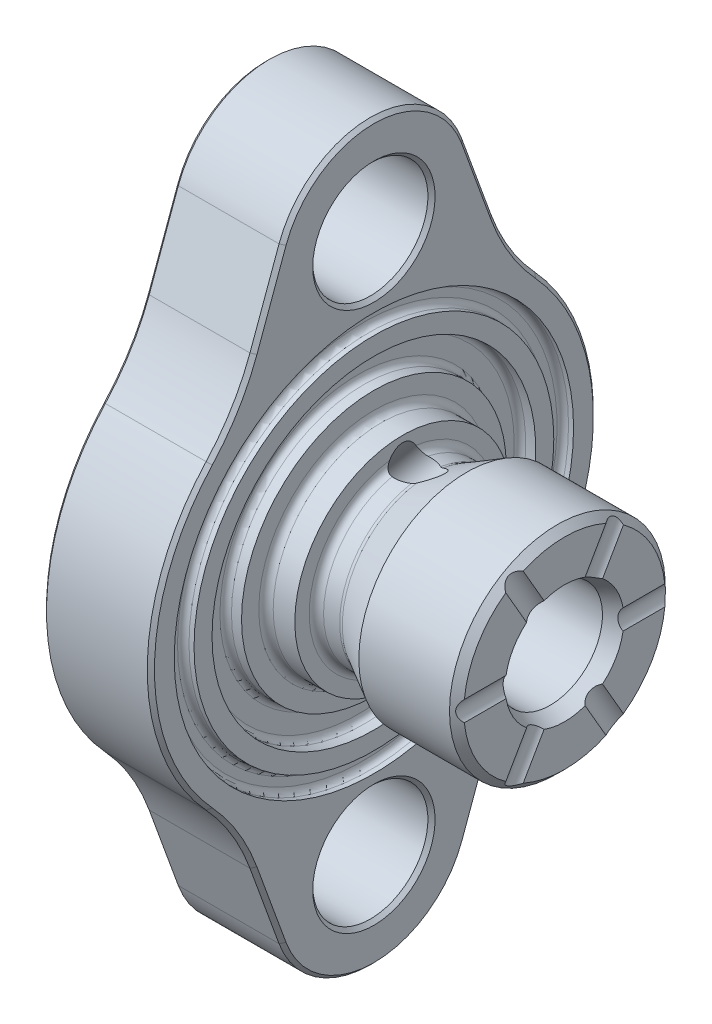
SolidWorks part; units mm, degrees
material "17CrNiMo6"
ref_plane "Front Plane" through (0, 0, 0) normal (0, 0, 1) x (1, 0, 0)
ref_plane "Top Plane" through (0, 0, 0) normal (0, 1, 0) x (1, 0, 0)
ref_plane "Right Plane" through (0, 0, 0) normal (1, 0, 0) x (0, 0, -1)
sketch "Sketch1" plane through (0, 0, 0) normal (0, 0, 1) x (1, 0, 0)
  line L0 (0, 0) -> (0, 52.5)
  line L1 (0, 52.5) -> (15, 52.5)
  line L2 (15, 52.5) -> (15, 27.75)
  line L3 (15, 27.75) -> (14.3, 27.75)
  line L4 (13.5, 26.95) -> (13.5, 25.8)
  line L5 (14.3, 25) -> (15, 25)
  line L6 (15, 25) -> (15, 22.5)
  line L7 (15, 22.5) -> (13.6, 22.5)
  line L8 (12.8, 21.7) -> (12.8, 19.2)
  line L9 (13.6, 18.4) -> (15, 18.4)
  line L10 (15, 18.4) -> (15, 15.9975)
  line L11 (16, 14.9975) -> (19, 14.9975)
  line L12 (19, 14.9975) -> (19, 13)
  line L13 (20, 12) -> (22.2411, 12)
  line L14 (22.7264, 12.1257) -> (27.9, 14.9975)
  line L15 (27.9, 14.9975) -> (41.5, 14.9975)
  line L16 (41.5, 14.9975) -> (41.5, 8.25)
  line L17 (41.5, 8.25) -> (39.5, 7.265)
  line L18 (39.5, 7.265) -> (30, 7.265)
  line L19 (30, 7.265) -> (30, 7.5)
  line L20 (30, 7.5) -> (28.5, 7.5)
  line L21 (28.5, 7.5) -> (27.9082, 6.515)
  line L22 (27.9082, 6.515) -> (19, 6.515)
  line L23 (19, 6.515) -> (19, 6.9)
  line L24 (12.5, 6.9) -> (8.5163, 0)
  line L25 (0, 0) -> (64.1591, 0) construction
  line L26 (19, 6.9) -> (12.5, 6.9)
  line L27 (0, 0) -> (8.5163, 0)
  arc A0 (14.3, 27.75) -> (13.5, 26.95) centre (14.3, 26.95) ccw
  arc A1 (14.3, 25) -> (13.5, 25.8) centre (14.3, 25.8) cw
  arc A2 (13.6, 22.5) -> (12.8, 21.7) centre (13.6, 21.7) ccw
  arc A3 (13.6, 18.4) -> (12.8, 19.2) centre (13.6, 19.2) cw
  arc A4 (20, 12) -> (19, 13) centre (20, 13) cw
  arc A5 (22.7264, 12.1257) -> (22.2411, 12) centre (22.2411, 13) cw
  arc A6 (16, 14.9975) -> (15, 15.9975) centre (16, 15.9975) cw
  point P25 (21, 12)
  point P42 (22.5, 12)
  dimension "D29" = 0.8
  dimension "D30" = 1
  dimension "D31" = 1
  dimension "D1" = 60
  dimension "D2" = 15
  dimension "D3" = 105
  dimension "D4" = 11.5
  dimension "D5" = 14.53
  dimension "D6" = 13.8
  dimension "D7" = 15
  dimension "D8" = 29.995
  dimension "D9" = 24
  dimension "D10" = 26.5
  dimension "D11" = 13
  dimension "D12" = 59
  dimension "D13" = 2
  dimension "D14" = 16.5
  dimension "D15" = 13.03
  dimension "D16" = 29
  dimension "D17" = 22.5
  dimension "D18" = 13.6
  dimension "D19" = 19
  dimension "D20" = 36.8
  dimension "D21" = 45
  dimension "D22" = 50
  dimension "D23" = 55.5
  dimension "D24" = 1.5
  dimension "D25" = 2.2
  dimension "D26" = 2
  dimension "D27" = 41.5
  dimension "D28" = 22.5
  dimension "D32" = 32.9837
revolve "Revolve1" add sketch "Sketch1" angle 360 about L25
sketch "Sketch2" plane through (0, 0, 0) normal (-1, 0, 0) x (0, 0, 1)
  line L0 (0, 0) -> (70.5057, 0) construction
  line L1 (0, 0) -> (0, 55.746) construction
  line L2 (12.6859, 42.1173) -> (16.7286, 31.0098)
  line L3 (-12.6859, 42.1173) -> (-16.7286, 31.0098)
  line L4 (12.6859, -42.1173) -> (16.7286, -31.0098)
  line L5 (-12.6859, -42.1173) -> (-16.7286, -31.0098)
  arc A0 (12.6859, 42.1173) -> (-12.6859, 42.1173) centre (0, 37.5) ccw
  arc A1 (22.8279, -20.9735) -> (22.8279, 20.9735) centre (0, 0) ccw
  arc A2 (22.8279, 20.9735) -> (16.7286, 31.0098) centre (44.9194, 41.2704) cw
  arc A3 (-22.8279, 20.9735) -> (-16.7286, 31.0098) centre (-44.9194, 41.2704) ccw
  arc A4 (-22.8279, -20.9735) -> (-22.8279, 20.9735) centre (0, 0) cw
  arc A5 (22.8279, -20.9735) -> (16.7286, -31.0098) centre (44.9194, -41.2704) ccw
  arc A6 (12.6859, -42.1173) -> (-12.6859, -42.1173) centre (0, -37.5) cw
  arc A7 (-22.8279, -20.9735) -> (-16.7286, -31.0098) centre (-44.9194, -41.2704) cw
  circle A8 centre (0, 37.5) radius 8 construction
  circle A9 centre (0, -37.5) radius 8 construction
  dimension "D1" = 27
  dimension "D2" = 62
  dimension "D3" = 75
  dimension "D5" = 30
  dimension "D6" = 102
  dimension "D7" = 16
  dimension "D4" = 20
extrude "Cut-Extrude1" cut sketch "Sketch2" against normal through all flip side to cut
sketch "Sketch3" plane through (0, 0, 0) normal (-1, 0, 0) x (0, 0, 1)
  circle A0 centre (0, 37.5) radius 8
  dimension "D1" = 16
extrude "Cut-Extrude2" cut sketch "Sketch3" against normal through all
mirror "Mirror1" about plane through (0, 0, 0) normal (0, 1, 0) of "Cut-Extrude2"
hole_wizard "CENTRE Hole1" positions "Sketch7" profile "Sketch6" legacy
sketch "Sketch7" plane through (0, 0, 0) normal (-1, 0, 0) x (0, 0, 1)
  point P0 (0, 0)
sketch "Sketch6" plane through (0, 0, 0) normal (0, 1, 0) x (0, 0, 1)
  line L0 (0, 0) -> (0, 6.2017)
  line L1 (0, 6.2017) -> (2, 5)
  line L2 (2, 5) -> (2, 1.7321)
  line L3 (2, 1.7321) -> (3, 0)
  line L4 (3, 0) -> (0, 0)
  line L5 (0, -14.3089) -> (0, 102.4216) construction
  line L6 (0, 6.2017) -> (-2, 5) construction
  line L7 (-2, 1.7321) -> (-3, 0) construction
  dimension "Diameter" = 4
  dimension "Depth" = 5
  dimension "C-Sink Diameter" = 6
  dimension "C-Sink Angle" = 60
  dimension "Drill Angle" = 118
chamfer "Chamfer2" distance 1 angle 45 1 edges at (41.5, 0, 14.9975)
sketch "Sketch8" plane through (0, 0, 0) normal (0, 0, 1) x (1, 0, 0)
  line L0 (0, 0) -> (52.9452, 0) construction
  line L2 (45.4183, -1.4) -> (41.5, -1.4)
  line L3 (45.4183, -1.4) -> (45.4183, 1.4)
  line L4 (45.4183, 1.4) -> (41.5, 1.4)
  line L5 (40.9283, -1.4) -> (40.9283, 1.4) construction
  line L6 (41.5, 1.4) -> (41.5, -1.4) construction
  line L7 (41.5, -13.9975) -> (41.5, 13.9975) construction
  arc A0 (41.5, 1.4) -> (41.5, -1.4) centre (42.9283, 0) ccw
  dimension "D2" = 2
  dimension "D1" = 2.8
extrude "Cut-Extrude4" cut sketch "Sketch8" against normal through all
ref_axis "Axis1" through (30, 0, 0) along (1, 0, 0)
pattern_circular "CirPattern1" count 6 over 360 about axis through (30, 0, 0) along (1, 0, 0) of "Cut-Extrude4"
ref_plane "Plane1" through (0, 0, 0) normal (0.6428, 0.766, 0) x (0, 0, -1)
ref_plane "Plane2" through (14.5855, 17.3824, 0) normal (0.6428, 0.766, 0) x (0, 0, -1)
sketch "Sketch14" plane through (0, 0, 0) normal (0, 0, 1) x (1, 0, 0)
  line L0 (20.5, 12) -> (10.4308, 0) construction
  line L1 (0, 0) -> (45.7767, 0) construction
  line L2 (41.5, 12.7614) -> (41.5, 7.7411) construction
  line L4 (0, 0) -> (64.1591, 0) construction
  line L5 (20, 12) -> (22.2411, 12) construction
  line L6 (25.8044, 14.4322) -> (15.5826, 2.2504)
  line L7 (25.8044, 14.4322) -> (23.8893, 16.0392)
  line L8 (15.5826, 2.2504) -> (12.3191, 2.2504)
  line L9 (23.8893, 16.0392) -> (12.3191, 2.2504)
  dimension "D1" = 50
  dimension "D2" = 21
  dimension "D3" = 5
  dimension "D4" = 5.2728
  dimension "D5" = 18
revolve "Cut-Revolve1" cut sketch "Sketch14" angle 360 about L9
pattern_circular "CirPattern2" count 2 over 360 about axis through (30, 0, 0) along (1, 0, 0) of "Cut-Revolve1"
sketch "Sketch13" plane through (0, 0, 0) normal (-1, 0, 0) x (0, 0, 1)
  line L0 (8, 16.3705) -> (8, -17.6011) construction
  line L1 (12.8425, 6.2687) -> (12.8425, -4.52) construction
  text T0 "3115 2076 03 - A\r\n11111 - XX" font "Century Gothic" height 3
  line B0 (12.8425, -2.4498) -> (12.8425, 1.4724)
  line B1 (13.642, -1.8688) -> (13.642, 1.0177)
  line B2 (12.9625, 1.4041) -> (13.522, 1.086)
  line B3 (16.9756, -0.0372) -> (16.9756, 0.6468)
  line B4 (19.6923, 1.4724) -> (16.9756, -0.0372)
  line B5 (13.642, -1.8688) -> (16.2187, -0.4475)
  line B6 (16.2187, -3.6028) -> (15.5991, -3.9613)
  line B7 (19.6923, -0.4525) -> (19.6923, 1.4724)
  line B8 (16.9756, -3.19) -> (16.2187, -3.6028)
  line B9 (16.9756, -3.19) -> (18.7235, -2.1534)
  line B10 (12.8425, 1.4724) -> (12.8425, 4.4693)
  line B11 (15.8055, 2.7844) -> (12.8425, 4.4693)
  line B12 (16.3391, -3.4279) -> (16.8556, -3.1217)
  line B13 (19.5723, -0.4525) -> (19.5723, 1.2684)
  line B14 (19.5723, 1.2684) -> (16.9756, -0.1745)
  line B15 (16.8556, 0.6468) -> (16.8556, -3.1217)
  line B16 (15.7434, 2.6817) -> (12.9625, 4.263)
  line B17 (12.9625, 1.5422) -> (12.9625, 4.263)
  line B18 (16.3391, -0.3779) -> (16.3391, -3.4279)
  line B19 (12.9625, 1.5422) -> (16.3391, -0.3779)
  line B20 (16.2187, -3.4641) -> (15.5367, -3.8587)
  line B21 (12.9625, -2.4498) -> (12.9625, 1.4041)
  line B22 (16.9756, -0.1745) -> (16.9756, -3.0505)
  line B23 (16.9756, -3.0505) -> (18.6622, -2.0502)
  line B24 (13.522, -2.0721) -> (13.522, 1.086)
  line B25 (13.522, -2.0721) -> (16.2187, -0.5845)
  line B26 (16.2187, -0.5845) -> (16.2187, -3.4641)
  line B27 (13.642, 1.0177) -> (16.2187, -0.4475)
  arc B28 (18.7235, -2.1534) -> (19.6923, -0.4525) centre (17.7147, -0.4525) ccw
  arc B29 (12.8425, -2.4498) -> (15.5991, -3.9613) centre (14.6352, -2.4498) ccw
  arc B30 (16.9756, 0.6468) -> (15.8055, 2.7844) centre (14.4379, 0.6468) ccw
  arc B31 (18.6622, -2.0502) -> (19.5723, -0.4525) centre (17.7147, -0.4525) ccw
  arc B32 (16.8556, 0.6468) -> (15.7434, 2.6817) centre (14.4379, 0.6468) ccw
  arc B33 (12.9625, -2.4498) -> (15.5367, -3.8587) centre (14.6352, -2.4498) ccw
  dimension "D1" = 8
sketch_block_instance "SKETCH LOGO-1"
sketch_block "SKETCH LOGO" parameters "D1"=29.059, "D2"=11.4163, "D3"=29.624, "D4"=6.8884
extrude "Extrude1" cut sketch "Sketch13" against normal blind 0.1
chamfer "Chamfer3" distance 0.5 angle 45 28 edges at (0, -25.6903, 19.2824) (0, 0, 31) (0, -36.5635, 14.7072) (0, 25.6903, 19.2824) (0, -51, 0) (0, 36.5635, 14.7072) (0, -36.5635, -14.7072) (0, 51, 0) (0, -25.6903, -19.2824) (0, 36.5635, -14.7072) (0, 0, -31) (0, 25.6903, -19.2824) (0, 37.5, 8) (0, -37.5, 8) (15, -25.6903, 19.2824) (15, 0, 31) (15, -36.5635, 14.7072) (15, 25.6903, 19.2824) (15, -51, 0) (15, 36.5635, 14.7072) (15, -36.5635, -14.7072) (15, 51, 0) (15, -25.6903, -19.2824) (15, 36.5635, -14.7072) (15, 0, -31) (15, 25.6903, -19.2824) (15, -37.5, 8) (15, 37.5, 8)
